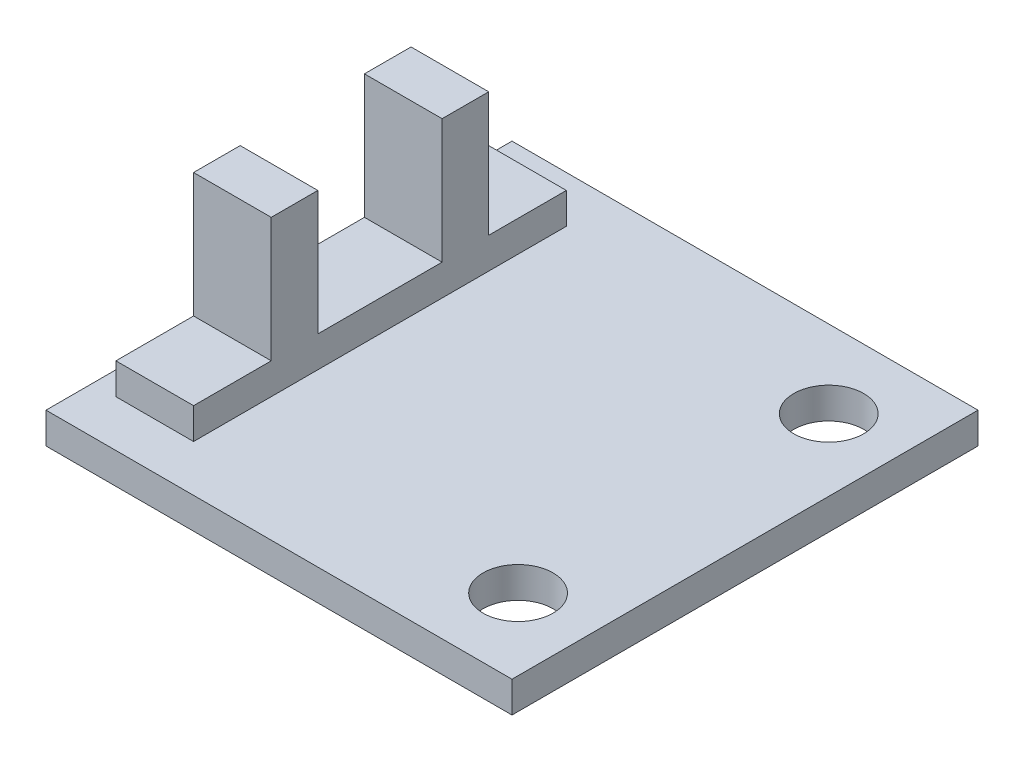
SolidWorks part; units mm, degrees
ref_plane "Front Plane" through (0, 0, 0) normal (0, 0, 1) x (1, 0, 0)
ref_plane "Top Plane" through (0, 0, 0) normal (0, 1, 0) x (1, 0, 0)
ref_plane "Right Plane" through (0, 0, 0) normal (1, 0, 0) x (0, 0, -1)
sketch "Sketch1" plane through (0, 0, 0) normal (0, 1, 0) x (1, 0, 0)
  line L1 (0, 0) -> (30, 0)
  line L2 (0, 0) -> (0, 30)
  line L3 (0, 30) -> (30, 30)
  line L4 (30, 0) -> (30, 30)
  dimension "D1" = 30
  dimension "D2" = 30
extrude "Boss-Extrude1" add sketch "Sketch1" along normal blind 2
sketch "Sketch2" plane through (0, 2, 0) normal (0, 1, 0) x (1, 0, 0)
  line L1 (1.5, 3) -> (6.5, 3)
  line L2 (1.5, 3) -> (1.5, 27)
  line L3 (1.5, 27) -> (6.5, 27)
  line L4 (6.5, 3) -> (6.5, 27)
  dimension "D1" = 3
  dimension "D2" = 3
  dimension "D3" = 1.5
  dimension "D4" = 5
extrude "Boss-Extrude2" add sketch "Sketch2" along normal blind 10
sketch "Sketch3" plane through (0, 12, 0) normal (0, 1, 0) x (1, 0, 0)
  line L0 (1.5, 27) -> (1.5, 3) construction
  line L1 (6.5, 27) -> (1.5, 27)
  line L2 (6.5, 27) -> (6.5, 22)
  line L3 (6.5, 22) -> (1.5, 22)
  line L4 (1.5, 27) -> (1.5, 22)
  line L5 (6.5, 3) -> (6.5, 27) construction
  line L6 (6.5, 3) -> (1.5, 3)
  line L7 (6.5, 3) -> (6.5, 8)
  line L8 (6.5, 8) -> (1.5, 8)
  line L9 (1.5, 3) -> (1.5, 8)
  line L10 (1.5, 11) -> (6.5, 11)
  line L11 (1.5, 11) -> (1.5, 19)
  line L12 (1.5, 19) -> (6.5, 19)
  line L13 (6.5, 11) -> (6.5, 19)
  dimension "D1" = 5
  dimension "D2" = 5
  dimension "D3" = 3
  dimension "D4" = 3
extrude "Cut-Extrude1" cut sketch "Sketch3" against normal blind 8
sketch "Sketch4" plane through (0, 0, 0) normal (0, -1, 0) x (1, 0, 0)
  circle A0 centre (25.3909, -5) radius 2.25
  circle A1 centre (25.3909, -25) radius 2.25
extrude "Cut-Extrude2" cut sketch "Sketch4" against normal blind 10
